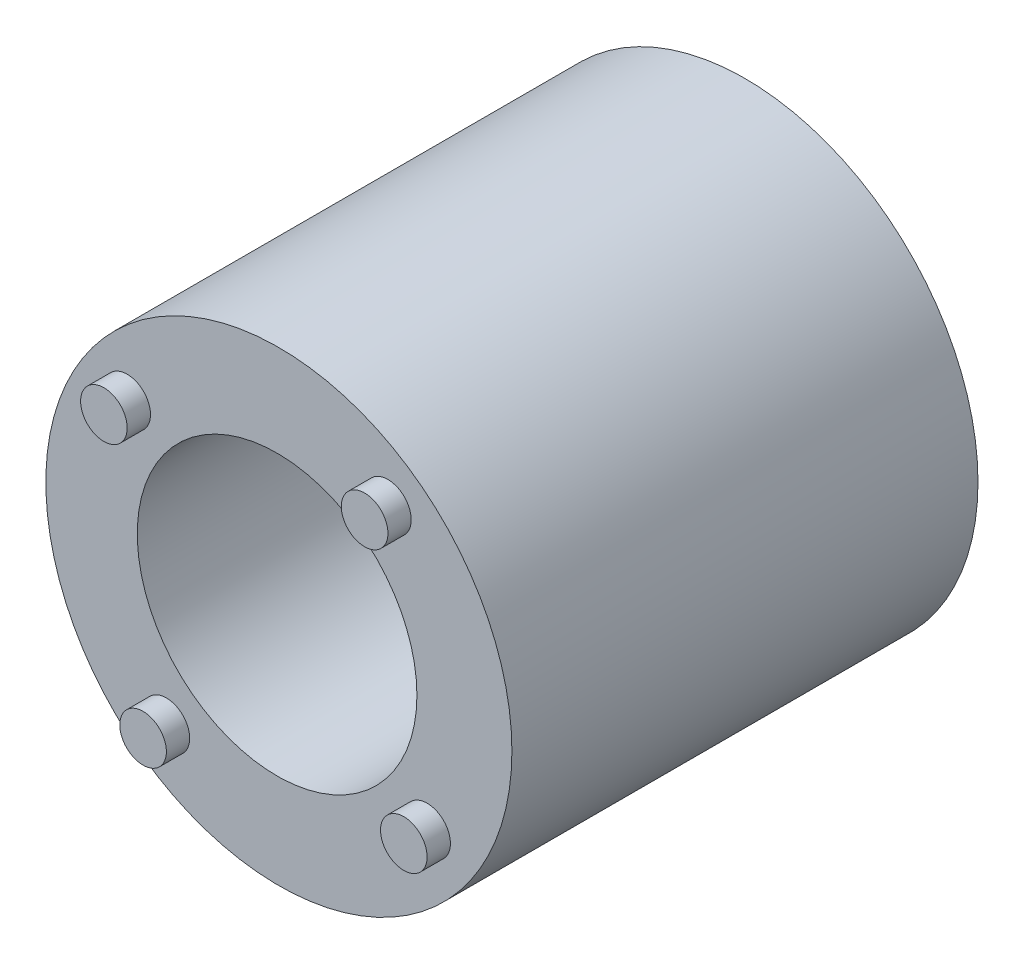
SolidWorks part; units mm, degrees
ref_plane "Front Plane" through (0, 0, 0) normal (0, 0, 1) x (1, 0, 0)
ref_plane "Top Plane" through (0, 0, 0) normal (0, 1, 0) x (1, 0, 0)
ref_plane "Right Plane" through (0, 0, 0) normal (1, 0, 0) x (0, 0, -1)
sketch "Sketch1" plane through (0, 0, 0) normal (0, 0, 1) x (1, 0, 0)
  circle A0 centre (0.3694, 0) radius 50
  dimension "D1" = 100
extrude "Boss-Extrude1" add sketch "Sketch1" along normal blind 100
sketch "Sketch3" plane through (0, 0, 0) normal (0, 0, -1) x (-1, 0, 0)
  circle A0 centre (0, 35) radius 5
  circle A1 centre (35, 0) radius 5
  circle A2 centre (0, -35) radius 5
  circle A3 centre (-35, 0) radius 5
  dimension "D2" = 10
  dimension "D1" = 35
  dimension "D3" = 4
extrude "Boss-Extrude3" add sketch "Sketch3" along normal blind 5
sketch "Sketch4" plane through (0, 0, 100) normal (0, 0, 1) x (1, 0, 0)
  circle A0 centre (23.7648, 32.175) radius 5
  circle A1 centre (32.175, -23.7648) radius 5
  circle A2 centre (-23.7648, -32.175) radius 5
  circle A3 centre (-32.175, 23.7648) radius 5
  dimension "D1" = 10
  dimension "D2" = 40
  dimension "D3" = 4
extrude "Boss-Extrude4" add sketch "Sketch4" along normal blind 5
sketch "Sketch5" plane through (0, 0, 100) normal (0, 0, 1) x (1, 0, 0)
  circle A0 centre (-0.0095, 0.1894) radius 30
  dimension "D1" = 60
extrude "Cut-Extrude1" cut sketch "Sketch5" against normal through all
